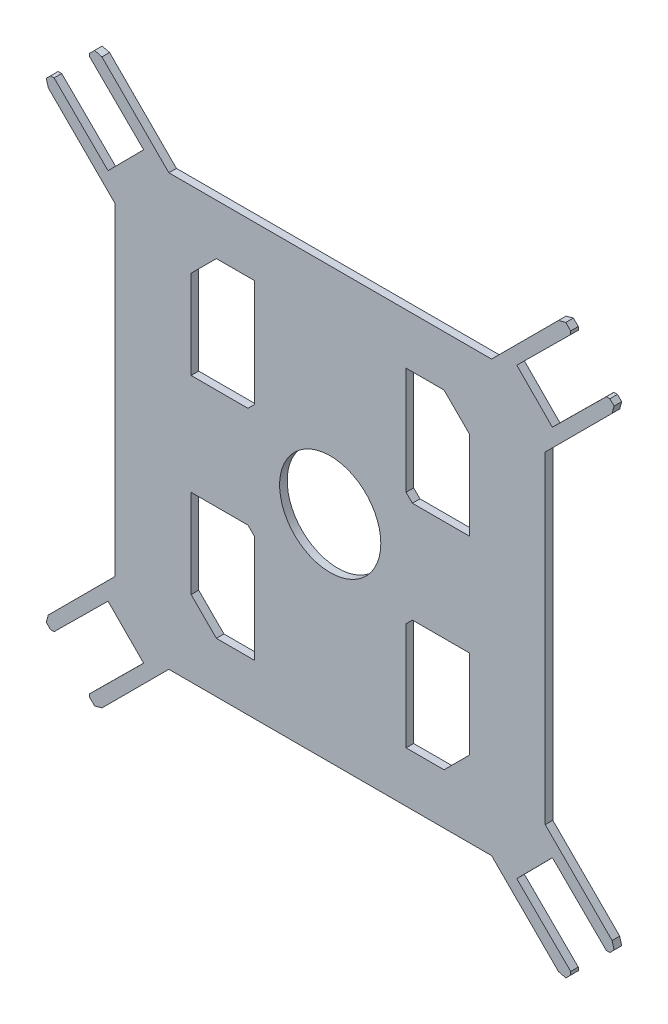
SolidWorks part; units mm, degrees
ref_plane "Front Plane" through (0, 0, 0) normal (0, 0, 1) x (1, 0, 0)
ref_plane "Top Plane" through (0, 0, 0) normal (0, 1, 0) x (1, 0, 0)
ref_plane "Right Plane" through (0, 0, 0) normal (1, 0, 0) x (0, 0, -1)
sketch "Sketch1" plane through (0, 0, 0) normal (0, 0, 1) x (1, 0, 0)
  line L0 (-25.5585, 109.7968) -> (-24.1443, 109.7968)
  line L1 (21.2132, -70) -> (148.7868, -70)
  line L2 (0, -48.7868) -> (0, 78.7868)
  line L3 (21.2132, 100) -> (148.7868, 100)
  line L4 (170, -48.7868) -> (170, 78.7868)
  line L5 (-24.1443, 109.7968) -> (-2.8287, 88.6865)
  line L7 (21.2132, 100) -> (-5.234, 126.4472)
  line L8 (-8.1317, 127.2236) -> (-10.0706, 125.2848)
  line L9 (-26.4472, 105.234) -> (0, 78.7868)
  line L10 (197.2236, -78.1317) -> (195.5585, -79.7968)
  line L11 (170, -48.7868) -> (196.4472, -75.2339)
  line L13 (175.2339, -96.4472) -> (148.7868, -70)
  line L15 (178.1317, 127.2236) -> (180.0706, 125.2848)
  line L16 (148.7868, 100) -> (175.2339, 126.4472)
  line L18 (196.4472, 105.234) -> (170, 78.7868)
  line L19 (0, -48.7868) -> (-26.4472, -75.2339)
  line L21 (-5.234, -96.4472) -> (21.2132, -70)
  line L22 (-27.2236, -78.1317) -> (-25.5585, -79.7968)
  line L23 (-2.8287, 88.6865) -> (11.245, 102.8971)
  line L24 (11.245, 102.8971) -> (-10.0706, 124.0074)
  line L25 (-27.2236, 108.1317) -> (-26.4472, 105.234)
  line L26 (-10.0706, 124.0074) -> (-10.0706, 125.2848)
  line L27 (-8.1317, 127.2236) -> (-5.234, 126.4472)
  line L29 (-25.5585, 109.7968) -> (-27.2236, 108.1317)
  line L30 (-8.1317, -97.2236) -> (-5.234, -96.4472)
  line L31 (-8.1317, -97.2236) -> (-10.0706, -95.2848)
  line L32 (-10.0706, -94.0074) -> (-10.0706, -95.2848)
  line L33 (11.245, -72.8971) -> (-10.0706, -94.0074)
  line L34 (-2.8287, -58.6865) -> (11.245, -72.8971)
  line L35 (-27.2236, -78.1317) -> (-26.4472, -75.2339)
  line L36 (-25.5585, -79.7968) -> (-24.1443, -79.7968)
  line L37 (-24.1443, -79.7968) -> (-2.8287, -58.6865)
  line L38 (-10.0706, -95.2848) -> (-8.1317, -97.2236)
  line L39 (195.5585, 109.7968) -> (194.1443, 109.7968)
  line L40 (195.5585, 109.7968) -> (197.2236, 108.1317)
  line L41 (197.2236, 108.1317) -> (196.4472, 105.234)
  line L42 (194.1443, 109.7968) -> (172.8287, 88.6865)
  line L43 (178.1317, 127.2236) -> (175.2339, 126.4472)
  line L44 (180.0706, 124.0074) -> (180.0706, 125.2848)
  line L45 (158.755, 102.8971) -> (180.0706, 124.0074)
  line L46 (195.5585, 109.7968) -> (197.2236, 108.1317)
  line L47 (172.8287, 88.6865) -> (158.755, 102.8971)
  line L48 (178.1317, -97.2236) -> (175.2339, -96.4472)
  line L49 (178.1317, -97.2236) -> (180.0706, -95.2848)
  line L50 (180.0706, -94.0074) -> (180.0706, -95.2848)
  line L51 (197.2236, -78.1317) -> (196.4472, -75.2339)
  line L52 (195.5585, -79.7968) -> (197.2236, -78.1317)
  line L53 (195.5585, -79.7968) -> (194.1443, -79.7968)
  line L54 (194.1443, -79.7968) -> (172.8287, -58.6865)
  line L55 (172.8287, -58.6865) -> (158.755, -72.8971)
  line L56 (158.755, -72.8971) -> (180.0706, -94.0074)
  line L57 (180.0706, -95.2848) -> (178.1317, -97.2236)
  dimension "D1" = 5
  dimension "D2" = 5
  dimension "D3" = 127.5736
  dimension "D4" = 30
  dimension "D5" = 30
  dimension "D6" = 127.5736
  dimension "D7" = 1
  dimension "D8" = 45
  dimension "D9" = 30
  dimension "D10" = 30
  dimension "D11" = 127.5736
  dimension "D12" = 127.5736
extrude "Boss-Extrude1" add sketch "Sketch1" along normal blind 3 contours L56 L55 L54 L53 L10 L51 L11 L4 L18 L41 L40 L39 L42 L47 L45 L44 L15 L43 L16 L3 L7 L27 L8 L26 L24 L23 L5 L0 L29 L25 L9 L2 L19 L35 L22 L36 L37 L34 L33 L32 L31 L30 L21 L1 L13 L48 L49 L50
sketch "Sketch2" plane through (0, 0, 3) normal (0, 0, 1) x (1, 0, 0)
  line L0 (85, 100) -> (85, -70) construction
  line L1 (21.2132, 100) -> (148.7868, 100) construction
  line L2 (21.2132, -70) -> (148.7868, -70) construction
  line L3 (0, 15) -> (170, 15) construction
  line L4 (0, -48.7868) -> (0, 78.7868) construction
  line L5 (170, -48.7868) -> (170, 78.7868) construction
  line L6 (30, 70) -> (40, 80)
  line L7 (40, 80) -> (55, 80)
  line L8 (30, 70) -> (30, 35)
  line L9 (30, 35) -> (52.5, 35)
  line L10 (55, 80) -> (55, 37.5)
  line L11 (52.5, 35) -> (55, 37.5)
  line L12 (30, -5) -> (52.5, -5)
  line L13 (52.5, -5) -> (55, -7.5)
  line L14 (55, -50) -> (55, -7.5)
  line L15 (40, -50) -> (55, -50)
  line L16 (30, -40) -> (40, -50)
  line L17 (30, -40) -> (30, -5)
  line L18 (140, -40) -> (140, -5)
  line L19 (140, -40) -> (130, -50)
  line L20 (130, -50) -> (115, -50)
  line L21 (115, -50) -> (115, -7.5)
  line L22 (117.5, -5) -> (115, -7.5)
  line L23 (140, -5) -> (117.5, -5)
  line L24 (140, 35) -> (117.5, 35)
  line L25 (117.5, 35) -> (115, 37.5)
  line L26 (115, 80) -> (115, 37.5)
  line L27 (130, 80) -> (115, 80)
  line L28 (140, 70) -> (130, 80)
  line L29 (140, 70) -> (140, 35)
  circle A0 centre (85, 15) radius 20
  point P12 (30, 80)
  point P13 (55, 35)
  dimension "D1" = 30
  dimension "D2" = 30
  dimension "D3" = 20
  dimension "D4" = 20
extrude "Cut-Extrude1" cut sketch "Sketch2" against normal blind 10
